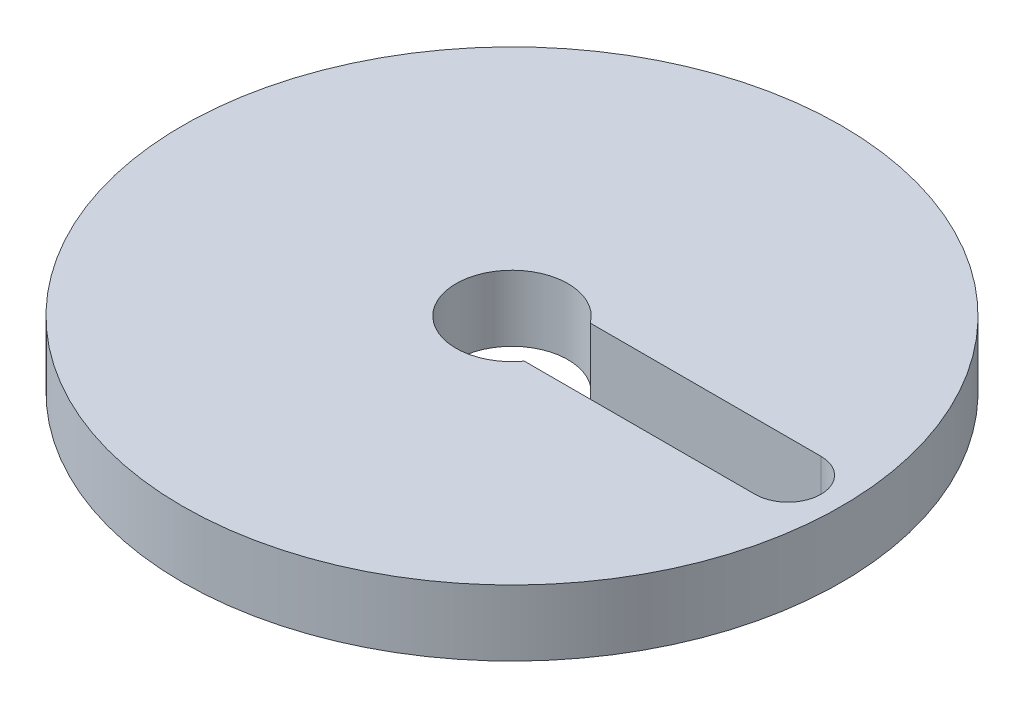
SolidWorks part; units mm, degrees
ref_plane "Front Plane" through (0, 0, 0) normal (0, 0, 1) x (1, 0, 0)
ref_plane "Top Plane" through (0, 0, 0) normal (0, 1, 0) x (1, 0, 0)
ref_plane "Right Plane" through (0, 0, 0) normal (1, 0, 0) x (0, 0, -1)
sketch "Sketch1" plane through (0, 0, 0) normal (0, 1, 0) x (1, 0, 0)
  line L0 (0, 0) -> (10, 0) construction
  line L1 (8.3748, 1) -> (1.3748, 1)
  line L2 (8.3748, -1) -> (1.3748, -1)
  circle A0 centre (0, 0) radius 10
  circle A1 centre (0, 0) radius 1.7
  arc A2 (8.3748, 1) -> (8.3748, -1) centre (8.3748, 0) cw
  point P10 (0, 0)
  dimension "D1" = 20
  dimension "D2" = 3.4
  dimension "D3" = 1
  dimension "D4" = 7
extrude "Boss-Extrude1" add sketch "Sketch1" along normal blind 2
